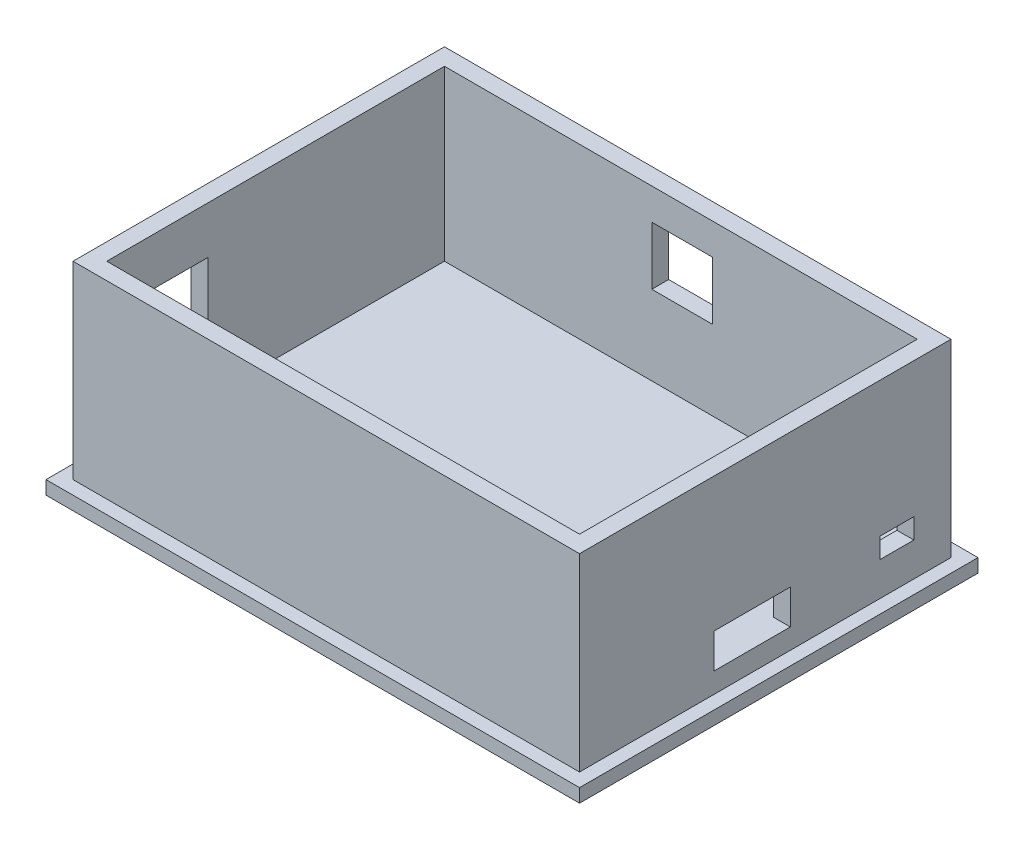
SolidWorks part; units mm, degrees
ref_plane "Front Plane" through (0, 0, 0) normal (0, 0, 1) x (1, 0, 0)
ref_plane "Top Plane" through (0, 0, 0) normal (0, 1, 0) x (1, 0, 0)
ref_plane "Right Plane" through (0, 0, 0) normal (1, 0, 0) x (0, 0, -1)
sketch "Sketch1" plane through (0, 0, 0) normal (0, 1, 0) x (1, 0, 0)
  line L1 (0, 0) -> (95.25, 0)
  line L2 (0, 0) -> (0, 69.85)
  line L3 (0, 69.85) -> (95.25, 69.85)
  line L4 (95.25, 0) -> (95.25, 69.85)
  dimension "D1" = 69.85
  dimension "D2" = 95.25
extrude "Boss-Extrude1" add sketch "Sketch1" along normal blind 38.1
sketch "Sketch2" plane through (0, 38.1, 0) normal (0, 1, 0) x (1, 0, 0)
  line L0 (0, 69.85) -> (0, 0) construction
  line L1 (3.175, 66.675) -> (92.075, 66.675)
  line L2 (3.175, 66.675) -> (3.175, 3.175)
  line L3 (3.175, 3.175) -> (92.075, 3.175)
  line L4 (92.075, 66.675) -> (92.075, 3.175)
  line L5 (95.25, 69.85) -> (0, 69.85) construction
  point P4 (0, 34.925)
  point P5 (47.625, 69.85)
  point P8 (47.625, 66.675)
  point P11 (3.175, 34.925)
  dimension "D1" = 3.175
  dimension "D2" = 3.175
extrude "Cut-Extrude1" cut sketch "Sketch2" against normal offset from surface (31.75 mm away) 6.35 up to face at (47.625, 0, -34.925)
sketch "Sketch3" plane through (95.25, 0, 0) normal (1, 0, 0) x (0, 0, -1)
  line L0 (3.175, 6.35) -> (66.675, 6.35) construction
  line L1 (62.865, 12.7) -> (56.515, 12.7)
  line L2 (62.865, 12.7) -> (62.865, 8.89)
  line L3 (62.865, 8.89) -> (56.515, 8.89)
  line L4 (56.515, 12.7) -> (56.515, 8.89)
  line L5 (66.675, 6.35) -> (66.675, 38.1) construction
  dimension "D1" = 3.81
  dimension "D2" = 6.35
  dimension "D3" = 2.54
  dimension "D4" = 3.81
extrude "Cut-Extrude2" cut sketch "Sketch3" against normal up to next contours L4 L3 L2 L1
sketch "Sketch4" plane through (0, 0, 0) normal (-1, 0, 0) x (0, 0, 1)
  line L0 (-66.675, 6.35) -> (-3.175, 6.35) construction
  line L1 (-6.985, 29.21) -> (-22.225, 29.21)
  line L2 (-6.985, 29.21) -> (-6.985, 19.05)
  line L3 (-6.985, 19.05) -> (-22.225, 19.05)
  line L4 (-22.225, 29.21) -> (-22.225, 19.05)
  line L5 (-3.175, 6.35) -> (-3.175, 38.1) construction
  dimension "D1" = 10.16
  dimension "D2" = 12.7
  dimension "D3" = 15.24
  dimension "D4" = 3.81
extrude "Cut-Extrude3" cut sketch "Sketch4" against normal up to next contours L4 L3 L2 L1
sketch "Sketch5" plane through (0, 0, 0) normal (0, -1, 0) x (1, 0, 0)
  line L8 (-2.54, 2.54) -> (-2.54, -72.39)
  line L9 (-2.54, -72.39) -> (97.79, -72.39)
  line L10 (97.79, -72.39) -> (97.79, 2.54)
  line L11 (97.79, 2.54) -> (-2.54, 2.54)
  line L12 (-2.54, 2.54) -> (-2.54, -72.39)
  line L13 (-2.54, -72.39) -> (97.79, -72.39)
  line L14 (97.79, -72.39) -> (97.79, 2.54)
  line L15 (97.79, 2.54) -> (-2.54, 2.54)
  dimension "D1" = 2.54
extrude "Boss-Extrude2" add sketch "Sketch5" against normal blind 2.54
sketch "Sketch6" plane through (0, 0, -69.85) normal (0, 0, -1) x (-1, 0, 0)
  line L0 (-42.164, 10.3487) -> (-42.164, 32.2078) construction
  line L1 (-53.594, 32.2078) -> (-42.164, 32.2078)
  line L2 (-53.594, 32.2078) -> (-53.594, 21.2783)
  line L3 (-53.594, 21.2783) -> (-42.164, 21.2783)
  line L4 (-42.164, 32.2078) -> (-42.164, 21.2783)
  point P7 (-42.164, 21.0898)
extrude "Cut-Extrude4" cut sketch "Sketch6" against normal blind 6.35
sketch "Sketch7" plane through (95.25, 0, 0) normal (1, 0, 0) x (0, 0, -1)
  line L1 (25.2733, 12.8518) -> (39.6356, 12.8518)
  line L2 (25.2733, 12.8518) -> (25.2733, 6.35)
  line L3 (25.2733, 6.35) -> (39.6356, 6.35)
  line L4 (39.6356, 12.8518) -> (39.6356, 6.35)
  line L5 (3.175, 6.35) -> (66.675, 6.35) construction
  point P5 (39.6356, 2.54)
  point P8 (25.2733, 9.676)
extrude "Cut-Extrude5" cut sketch "Sketch7" against normal blind 6.35
